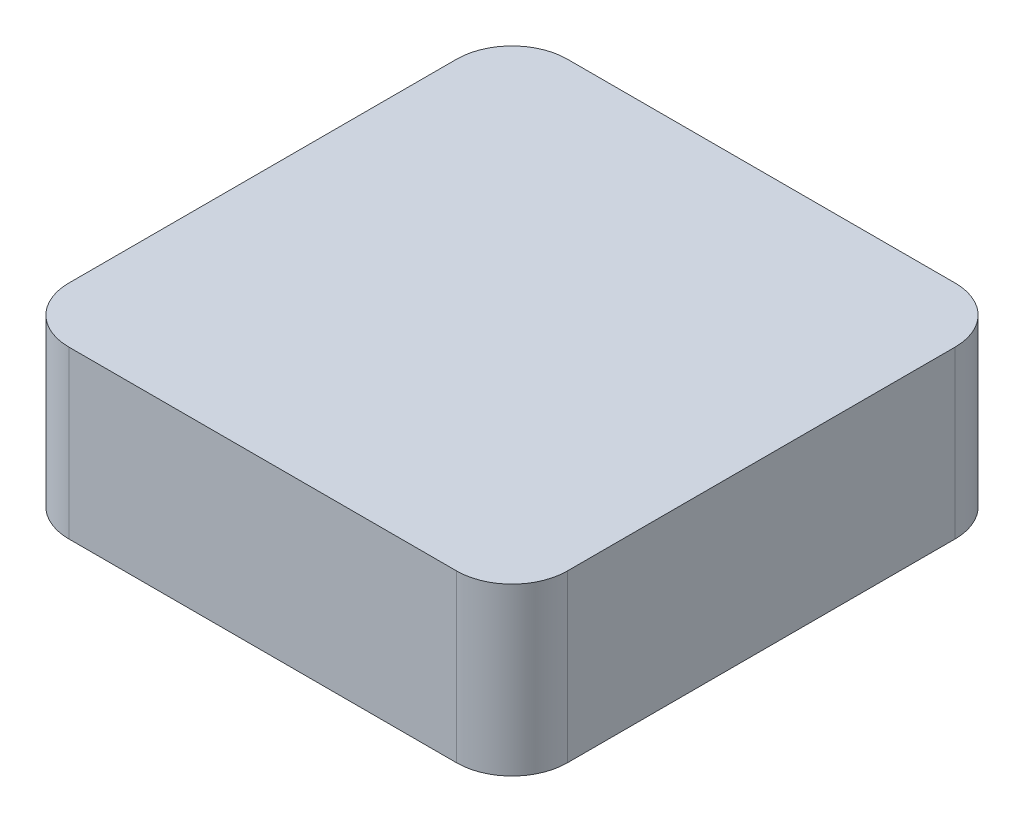
SolidWorks part; units mm, degrees
ref_plane "Front Plane" through (0, 0, 0) normal (0, 0, 1) x (1, 0, 0)
ref_plane "Top Plane" through (0, 0, 0) normal (0, 1, 0) x (1, 0, 0)
ref_plane "Right Plane" through (0, 0, 0) normal (1, 0, 0) x (0, 0, -1)
sketch "Sketch1" plane through (0, 0, 0) normal (0, 1, 0) x (1, 0, 0)
  line L1 (-8.4439, 7.0847) -> (9.5561, 7.0847)
  line L2 (-8.4439, 7.0847) -> (-8.4439, -10.9153)
  line L3 (-8.4439, -10.9153) -> (9.5561, -10.9153)
  line L4 (9.5561, 7.0847) -> (9.5561, -10.9153)
  dimension "D1" = 18
  dimension "D2" = 18
extrude "Boss-Extrude1" add sketch "Sketch1" along normal blind 6
sketch "Sketch2" plane through (0, 0, 0) normal (0, -1, 0) x (1, 0, 0)
  line L0 (-8.4439, 10.9153) -> (9.5561, 10.9153) construction
  line L1 (-6.4439, 8.9153) -> (7.5561, 8.9153)
  line L2 (-6.4439, 8.9153) -> (-6.4439, -5.0847)
  line L3 (-6.4439, -5.0847) -> (7.5561, -5.0847)
  line L4 (7.5561, 8.9153) -> (7.5561, -5.0847)
  line L5 (9.5561, -7.0847) -> (-8.4439, -7.0847) construction
  line L6 (9.5561, 10.9153) -> (9.5561, -7.0847) construction
  line L7 (-8.4439, -7.0847) -> (-8.4439, 10.9153) construction
  dimension "D1" = 2
  dimension "D2" = 2
  dimension "D3" = 2
  dimension "D4" = 2
extrude "Cut-Extrude1" cut sketch "Sketch2" against normal blind 4 draft 20
sketch "Sketch3" plane through (0, 4, 0) normal (0, -1, 0) x (1, 0, 0)
  line L0 (-4.9881, 7.4595) -> (-4.9881, -3.6288) construction
  line L1 (-4.9881, -3.6288) -> (6.1002, -3.6288) construction
  line L2 (6.1002, -3.6288) -> (6.1002, 7.4595) construction
  line L3 (6.1002, 7.4595) -> (-4.9881, 7.4595) construction
  line L4 (-4.9881, 7.4595) -> (-4.9881, -3.6288)
  line L5 (-4.9881, -3.6288) -> (6.1002, -3.6288)
  line L6 (6.1002, -3.6288) -> (6.1002, 7.4595)
  line L7 (6.1002, 7.4595) -> (-4.9881, 7.4595)
  line L9 (-1.4689, 1.2403) -> (2.5811, 1.2403)
  line L10 (-1.4689, 1.2403) -> (-1.4689, 2.5903)
  line L11 (-1.4689, 2.5903) -> (2.5811, 2.5903)
  line L12 (2.5811, 1.2403) -> (2.5811, 2.5903)
  line L13 (-0.1189, 3.9403) -> (1.2311, 3.9403)
  line L14 (-0.1189, 3.9403) -> (-0.1189, -0.1097)
  line L15 (-0.1189, -0.1097) -> (1.2311, -0.1097)
  line L16 (1.2311, 3.9403) -> (1.2311, -0.1097)
  circle A0 centre (0.5561, 1.9153) radius 3
  point P7 (-4.9881, 1.9153)
  point P8 (0.5561, -3.6288)
  point P16 (-1.4689, 1.9153)
  point P17 (0.5561, 1.2403)
  point P18 (0.5561, -0.1097)
  point P19 (-0.1189, 1.9153)
  dimension "D1" = 6
  dimension "D2" = 4.05
  dimension "D3" = 4.05
  dimension "D4" = 1.35
  dimension "D5" = 1.35
extrude "Boss-Extrude2" add sketch "Sketch3" along normal blind 4 contours A0 L13 L16 L11 L12 L9 L15 L14 L10
fillet "Fillet1" radius 2 4 edges at (-8.4439, 3, 10.9153) (9.5561, 3, 10.9153) (9.5561, 3, -7.0847) (-8.4439, 3, -7.0847)
